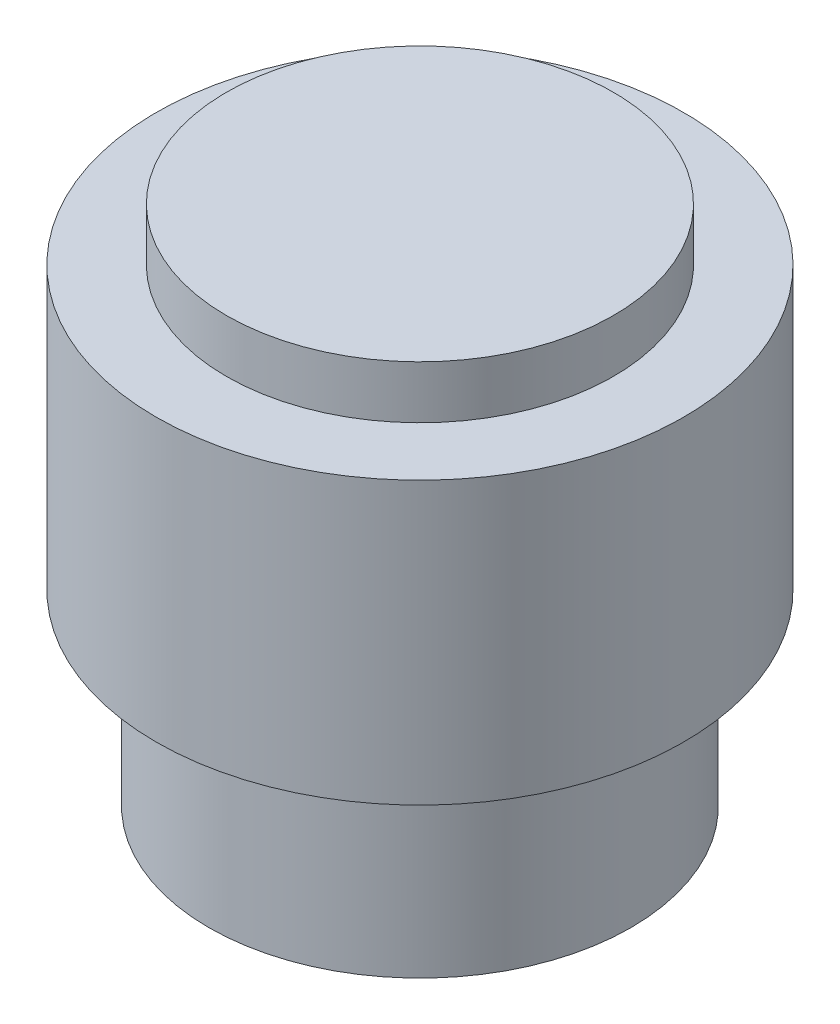
SolidWorks part; units mm, degrees
ref_plane "Front Plane" through (0, 0, 0) normal (0, 0, 1) x (1, 0, 0)
ref_plane "Top Plane" through (0, 0, 0) normal (0, 1, 0) x (1, 0, 0)
ref_plane "Right Plane" through (0, 0, 0) normal (1, 0, 0) x (0, 0, -1)
other "Configuration Table"
sketch "Sketch1" plane through (0, 0, 0) normal (0, 1, 0) x (1, 0, 0)
  circle A0 centre (0, 0) radius 6
extrude "Thread" add sketch "Sketch1" along normal blind 5.33 from offset 3.5
sketch "Sketch2" plane through (0, 0, 0) normal (0, 1, 0) x (1, 0, 0)
  circle A0 centre (0, 0) radius 7.5
extrude "Body" add sketch "Sketch2" along normal blind 8 from offset 1.82
sketch "Sketch3" plane through (0, 0, 0) normal (0, 1, 0) x (1, 0, 0)
  circle A0 centre (0, 0) radius 5.5
extrude "Front element" add sketch "Sketch3" along normal blind 1.51 from offset 9.81
